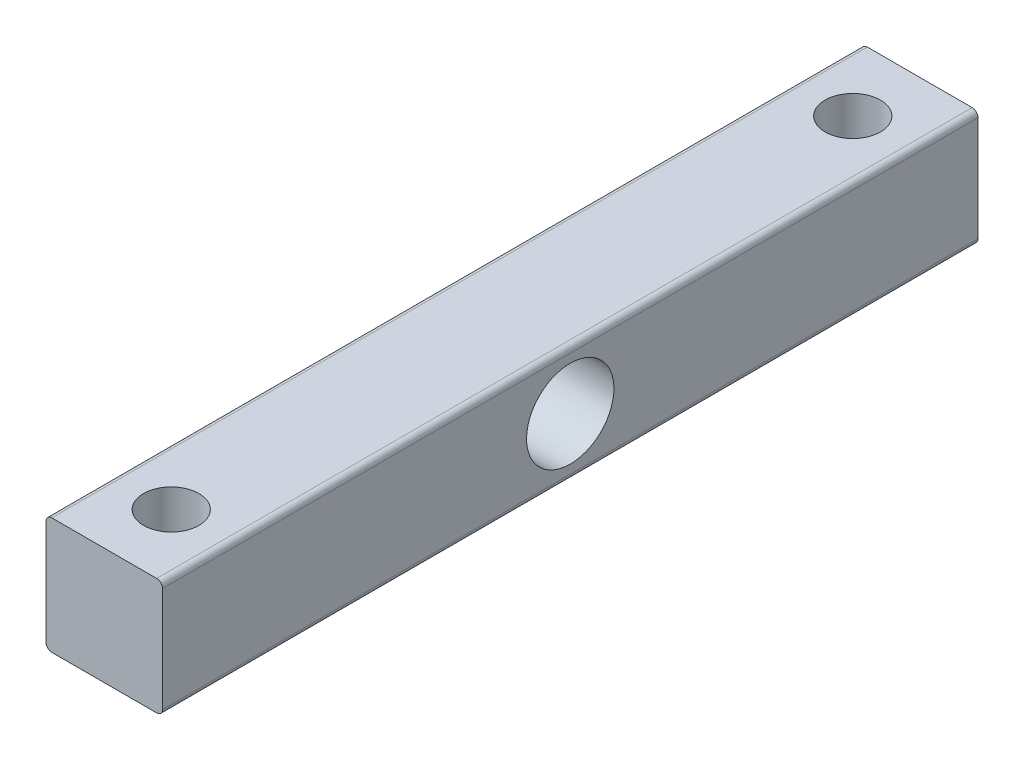
SolidWorks part; units mm, degrees
ref_plane "Front Plane" through (0, 0, 0) normal (0, 0, 1) x (1, 0, 0)
ref_plane "Top Plane" through (0, 0, 0) normal (0, 1, 0) x (1, 0, 0)
ref_plane "Right Plane" through (0, 0, 0) normal (1, 0, 0) x (0, 0, -1)
sketch "Sketch7" plane through (0, 0, 0) normal (0, 0, 1) x (1, 0, 0)
  line L1 (-0.091, 2.6837) -> (4.989, 2.6837)
  line L2 (-0.091, 2.6837) -> (-0.091, -2.3963)
  line L3 (-0.091, -2.3963) -> (4.989, -2.3963)
  line L4 (4.989, 2.6837) -> (4.989, -2.3963)
  dimension "D1" = 5.08
  dimension "D2" = 5.08
extrude "Boss-Extrude3" add sketch "Sketch7" along normal blind 17.78
sketch "Sketch8" plane through (0, 2.6837, 0) normal (0, 1, 0) x (1, 0, 0)
  line L0 (2.449, 0) -> (2.449, -14.859) construction
  line L1 (2.449, -14.859) -> (-0.091, -14.859) construction
  line L2 (-0.091, -17.78) -> (-0.091, 0) construction
  line L3 (4.989, 0) -> (-0.091, 0) construction
  circle A0 centre (2.449, -14.859) radius 1.2065
  dimension "D3" = 2.413
  dimension "D1" = 2.54
  dimension "D2" = 14.859
extrude "Cut-Extrude1" cut sketch "Sketch8" against normal up to surface (5.08 mm away) up to face at (2.449, -2.3963, 8.89)
mirror "Mirror2" about plane through (0, 0, 0) normal (0, 0, 1) of "Cut-Extrude1", "Boss-Extrude3"
fillet "Fillet1" radius 0.254 4 edges at (-0.091, -2.3963, 0) (4.989, -2.3963, 0) (4.989, 2.6837, 0) (-0.091, 2.6837, 0)
sketch "Sketch11" plane through (-0.091, 0, 0) normal (-1, 0, 0) x (0, 0, 1)
  line L0 (0, 2.6837) -> (0, 0.1437) construction
  line L1 (17.78, 2.6837) -> (-17.78, 2.6837) construction
  line L2 (17.78, 0.1437) -> (0, 0.1437) construction
  line L3 (17.78, 2.4297) -> (17.78, -2.1423) construction
  circle A0 centre (0, 0.1437) radius 1.905
  dimension "D1" = 3.81
  dimension "D2" = 2.54
  dimension "D3" = 17.78
extrude "Cut-Extrude2" cut sketch "Sketch11" against normal up to surface (5.08 mm away) up to face at (4.989, 0.1437, 0)
